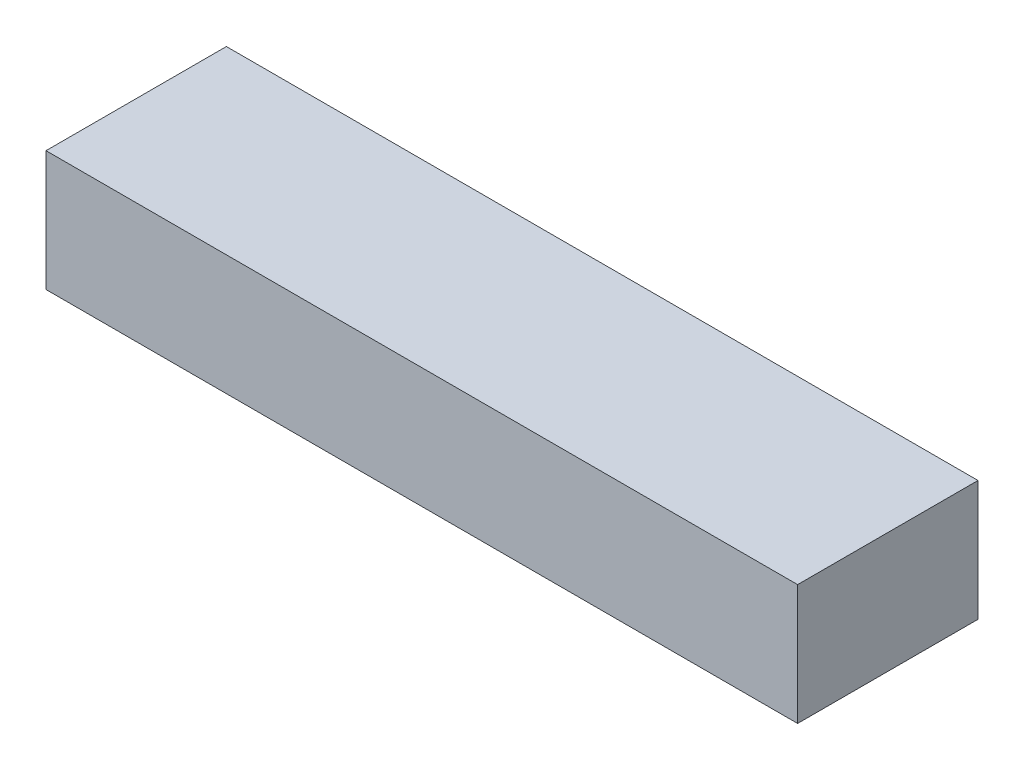
SolidWorks part; units mm, degrees
ref_plane "Front Plane" through (0, 0, 0) normal (0, 0, 1) x (1, 0, 0)
ref_plane "Top Plane" through (0, 0, 0) normal (0, 1, 0) x (1, 0, 0)
ref_plane "Right Plane" through (0, 0, 0) normal (1, 0, 0) x (0, 0, -1)
sketch "Sketch1" plane through (0, 0, 0) normal (0, 1, 0) x (1, 0, 0)
  line L1 (-25, -6) -> (25, -6)
  line L2 (-25, -6) -> (-25, 6)
  line L3 (-25, 6) -> (25, 6)
  line L4 (25, -6) -> (25, 6)
  line L5 (-25, -6) -> (25, 6) construction
  line L6 (-25, 6) -> (25, -6) construction
  point P0 (0, 0)
  dimension "D1" = 12
  dimension "D2" = 50
extrude "Boss-Extrude1" add sketch "Sketch1" along normal blind 8
